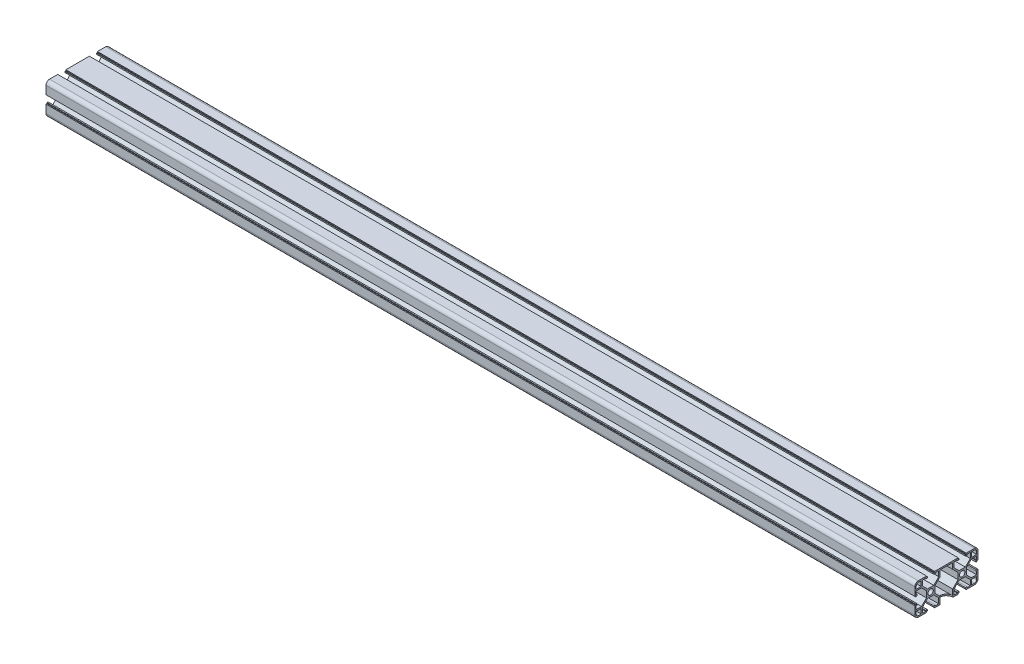
SolidWorks part; units mm, degrees
material "6063-T5"
ref_plane "前视基准面" through (0, 0, 0) normal (0, 0, 1) x (1, 0, 0)
ref_plane "上视基准面" through (0, 0, 0) normal (0, 1, 0) x (1, 0, 0)
ref_plane "右视基准面" through (0, 0, 0) normal (1, 0, 0) x (0, 0, -1)
sketch "草图1" plane through (0, 0, 0) normal (0, 1, 0) x (1, 0, 0)
  line L0 (0, 0) -> (1100, 0)
  dimension "D1" = 1100
ref_plane "基准面4" through (0, 0, 0) normal (1, 0, 0) x (0, 0, -1)
ref_plane "基准面5" through (0, 0, 0) normal (1, 0, 0) x (0, 0, -1)
ref_plane "基准面6" through (0, 0, 0) normal (1, 0, 0) x (0, 0, -1)
ref_plane "基准面7" through (0, 0, 0) normal (1, 0, 0) x (0, 0, -1)
ref_plane "基准面8" through (0, 0, 0) normal (1, 0, 0) x (0, 0, -1)
ref_plane "基准面10" through (0, 0, 0) normal (1, 0, 0) x (0, 0, -1)
other "欧标4080-厚2.0 欧标4080-厚2.0(1)"
ref_plane "基准面11" through (0, 0, 0) normal (1, 0, 0) x (0, 0, -1)
sketch "草图110" plane through (0, 0, 0) normal (1, 0, 0) x (0, 0, -1)
  line L0 (0, 20) -> (0, -20) construction
  line L1 (0, 0) -> (-20, 0) construction
  line L2 (-5.25, -3.9772) -> (-5.25, 3.9772)
  line L3 (-5.25, 3.9772) -> (-11.5228, 10.25)
  line L4 (-11.5228, 10.25) -> (-18.2, 10.25)
  line L5 (-18.2, 10.25) -> (-18.2, 6.1)
  line L6 (-18.2, 6.1) -> (-17.3, 6.1)
  line L7 (-17.3, 6.1) -> (-17.3, 4.1)
  line L8 (-17.3, 4.1) -> (-18.8, 4.1)
  line L9 (-18.8, 4.1) -> (-18.8, 5.1)
  line L10 (-18.8, 5.1) -> (-20, 5.1)
  line L11 (-20, 5.1) -> (-20, 15.5)
  line L12 (-20, 20) -> (0, 0) construction
  line L13 (-12.05, 12.05) -> (-18.2, 12.05)
  line L14 (-18.2, 12.05) -> (-18.2, 15.5)
  line L15 (-3.9772, 5.25) -> (-10.25, 11.5228)
  line L16 (3.9772, 5.25) -> (-3.9772, 5.25)
  line L17 (-12.05, 18.2) -> (-15.5, 18.2)
  line L18 (-12.05, 12.05) -> (-12.05, 18.2)
  line L19 (-5.1, 20) -> (-15.5, 20)
  line L20 (-5.1, 18.8) -> (-5.1, 20)
  line L21 (-4.1, 18.8) -> (-5.1, 18.8)
  line L22 (-4.1, 17.3) -> (-4.1, 18.8)
  line L23 (-6.1, 17.3) -> (-4.1, 17.3)
  line L24 (-6.1, 18.2) -> (-6.1, 17.3)
  line L25 (-10.25, 18.2) -> (-6.1, 18.2)
  line L26 (-10.25, 11.5228) -> (-10.25, 18.2)
  line L27 (3.9772, 5.25) -> (10.25, 11.5228)
  line L28 (5.25, 3.9772) -> (11.5228, 10.25)
  line L29 (5.25, -3.9772) -> (5.25, 3.9772)
  line L30 (20, 20) -> (20, -20) construction
  line L31 (12.05, 12.05) -> (12.05, 10.7772)
  line L32 (15.5, 20) -> (24.5, 20)
  line L33 (15.5, 18.2) -> (24.5, 18.2)
  line L34 (12.05, 10.7772) -> (11.5228, 10.25)
  line L35 (12.05, -10.7772) -> (11.5228, -10.25)
  line L36 (12.05, -12.05) -> (12.05, -10.7772)
  line L37 (15.5, -18.2) -> (24.5, -18.2)
  line L38 (15.5, -20) -> (24.5, -20)
  line L39 (60, -20) -> (40, 0) construction
  line L40 (10.25, 11.5228) -> (10.25, 18.2)
  line L41 (10.25, 18.2) -> (6.1, 18.2)
  line L42 (6.1, 18.2) -> (6.1, 17.3)
  line L43 (6.1, 17.3) -> (4.1, 17.3)
  line L44 (4.1, 17.3) -> (4.1, 18.8)
  line L45 (4.1, 18.8) -> (5.1, 18.8)
  line L46 (5.1, 18.8) -> (5.1, 20)
  line L47 (5.1, 20) -> (15.5, 20)
  line L48 (12.05, 12.05) -> (12.05, 18.2)
  line L49 (12.05, 18.2) -> (15.5, 18.2)
  line L50 (20, 20) -> (0, 0) construction
  line L51 (-17.3, -4.1) -> (-18.8, -4.1)
  line L52 (20, -20) -> (0, 0) construction
  line L53 (-20, -20) -> (0, 0) construction
  line L54 (12.05, -18.2) -> (15.5, -18.2)
  line L55 (12.05, -12.05) -> (12.05, -18.2)
  line L56 (5.1, -20) -> (15.5, -20)
  line L57 (5.1, -18.8) -> (5.1, -20)
  line L58 (4.1, -18.8) -> (5.1, -18.8)
  line L59 (4.1, -17.3) -> (4.1, -18.8)
  line L60 (6.1, -17.3) -> (4.1, -17.3)
  line L61 (6.1, -18.2) -> (6.1, -17.3)
  line L62 (10.25, -18.2) -> (6.1, -18.2)
  line L63 (10.25, -11.5228) -> (10.25, -18.2)
  line L64 (20, -20) -> (40, 0) construction
  line L65 (20, 20) -> (40, 0) construction
  line L66 (60, 20) -> (40, 0) construction
  line L67 (40, 0) -> (60, 0) construction
  line L68 (40, 20) -> (40, -20) construction
  line L69 (45.25, -3.9772) -> (51.5228, -10.25)
  line L70 (51.5228, -10.25) -> (58.2, -10.25)
  line L71 (58.2, -10.25) -> (58.2, -6.1)
  line L72 (58.2, -6.1) -> (57.3, -6.1)
  line L73 (5.25, -3.9772) -> (11.5228, -10.25)
  line L74 (3.9772, -5.25) -> (10.25, -11.5228)
  line L75 (-10.25, -11.5228) -> (-10.25, -18.2)
  line L76 (-10.25, -18.2) -> (-6.1, -18.2)
  line L77 (-6.1, -18.2) -> (-6.1, -17.3)
  line L78 (-6.1, -17.3) -> (-4.1, -17.3)
  line L79 (-4.1, -17.3) -> (-4.1, -18.8)
  line L80 (-4.1, -18.8) -> (-5.1, -18.8)
  line L81 (-5.1, -18.8) -> (-5.1, -20)
  line L82 (-5.1, -20) -> (-15.5, -20)
  line L83 (-12.05, -12.05) -> (-12.05, -18.2)
  line L84 (-12.05, -18.2) -> (-15.5, -18.2)
  line L85 (3.9772, -5.25) -> (-3.9772, -5.25)
  line L86 (-3.9772, -5.25) -> (-10.25, -11.5228)
  line L87 (-18.2, -12.05) -> (-18.2, -15.5)
  line L88 (-12.05, -12.05) -> (-18.2, -12.05)
  line L89 (-20, -5.1) -> (-20, -15.5)
  line L90 (-18.8, -5.1) -> (-20, -5.1)
  line L91 (-18.8, -4.1) -> (-18.8, -5.1)
  line L92 (-17.3, -6.1) -> (-17.3, -4.1)
  line L93 (-18.2, -6.1) -> (-17.3, -6.1)
  line L94 (-18.2, -10.25) -> (-18.2, -6.1)
  line L95 (-11.5228, -10.25) -> (-18.2, -10.25)
  line L96 (-5.25, -3.9772) -> (-11.5228, -10.25)
  line L97 (57.3, -6.1) -> (57.3, -4.1)
  line L98 (58.8, -4.1) -> (58.8, -5.1)
  line L99 (58.8, -5.1) -> (60, -5.1)
  line L100 (60, -5.1) -> (60, -15.5)
  line L101 (52.05, -12.05) -> (58.2, -12.05)
  line L102 (58.2, -12.05) -> (58.2, -15.5)
  line L103 (43.9772, -5.25) -> (50.25, -11.5228)
  line L104 (36.0228, -5.25) -> (43.9772, -5.25)
  line L105 (52.05, -18.2) -> (55.5, -18.2)
  line L106 (52.05, -12.05) -> (52.05, -18.2)
  line L107 (45.1, -20) -> (55.5, -20)
  line L108 (45.1, -18.8) -> (45.1, -20)
  line L109 (44.1, -18.8) -> (45.1, -18.8)
  line L110 (44.1, -17.3) -> (44.1, -18.8)
  line L111 (46.1, -17.3) -> (44.1, -17.3)
  line L112 (46.1, -18.2) -> (46.1, -17.3)
  line L113 (50.25, -18.2) -> (46.1, -18.2)
  line L114 (50.25, -11.5228) -> (50.25, -18.2)
  line L115 (36.0228, -5.25) -> (29.75, -11.5228)
  line L116 (34.75, -3.9772) -> (28.4772, -10.25)
  line L117 (29.75, -11.5228) -> (29.75, -18.2)
  line L118 (29.75, -18.2) -> (33.9, -18.2)
  line L119 (33.9, -18.2) -> (33.9, -17.3)
  line L120 (33.9, -17.3) -> (35.9, -17.3)
  line L121 (35.9, -17.3) -> (35.9, -18.8)
  line L122 (35.9, -18.8) -> (34.9, -18.8)
  line L123 (34.9, -18.8) -> (34.9, -20)
  line L124 (34.9, -20) -> (24.5, -20)
  line L125 (27.95, -12.05) -> (27.95, -18.2)
  line L126 (27.95, -18.2) -> (24.5, -18.2)
  line L127 (57.3, -4.1) -> (58.8, -4.1)
  line L128 (27.95, 18.2) -> (24.5, 18.2)
  line L129 (27.95, 12.05) -> (27.95, 18.2)
  line L130 (34.9, 20) -> (24.5, 20)
  line L131 (34.9, 18.8) -> (34.9, 20)
  line L132 (35.9, 18.8) -> (34.9, 18.8)
  line L133 (35.9, 17.3) -> (35.9, 18.8)
  line L134 (33.9, 17.3) -> (35.9, 17.3)
  line L135 (33.9, 18.2) -> (33.9, 17.3)
  line L136 (29.75, 18.2) -> (33.9, 18.2)
  line L137 (29.75, 11.5228) -> (29.75, 18.2)
  line L138 (27.95, -12.05) -> (27.95, -10.7772)
  line L139 (27.95, -10.7772) -> (28.4772, -10.25)
  line L140 (27.95, 10.7772) -> (28.4772, 10.25)
  line L141 (27.95, 12.05) -> (27.95, 10.7772)
  line L142 (34.75, -3.9772) -> (34.75, 3.9772)
  line L143 (34.75, 3.9772) -> (28.4772, 10.25)
  line L144 (36.0228, 5.25) -> (29.75, 11.5228)
  line L145 (50.25, 11.5228) -> (50.25, 18.2)
  line L146 (50.25, 18.2) -> (46.1, 18.2)
  line L147 (46.1, 18.2) -> (46.1, 17.3)
  line L148 (46.1, 17.3) -> (44.1, 17.3)
  line L149 (44.1, 17.3) -> (44.1, 18.8)
  line L150 (44.1, 18.8) -> (45.1, 18.8)
  line L151 (45.1, 18.8) -> (45.1, 20)
  line L152 (45.1, 20) -> (55.5, 20)
  line L153 (52.05, 12.05) -> (52.05, 18.2)
  line L154 (52.05, 18.2) -> (55.5, 18.2)
  line L155 (36.0228, 5.25) -> (43.9772, 5.25)
  line L156 (43.9772, 5.25) -> (50.25, 11.5228)
  line L157 (58.2, 12.05) -> (58.2, 15.5)
  line L158 (52.05, 12.05) -> (58.2, 12.05)
  line L159 (60, 5.1) -> (60, 15.5)
  line L160 (58.8, 5.1) -> (60, 5.1)
  line L161 (58.8, 4.1) -> (58.8, 5.1)
  line L162 (57.3, 4.1) -> (58.8, 4.1)
  line L163 (57.3, 6.1) -> (57.3, 4.1)
  line L164 (58.2, 6.1) -> (57.3, 6.1)
  line L165 (58.2, 10.25) -> (58.2, 6.1)
  line L166 (51.5228, 10.25) -> (58.2, 10.25)
  line L167 (45.25, 3.9772) -> (51.5228, 10.25)
  line L168 (45.25, -3.9772) -> (45.25, 3.9772)
  circle A0 centre (0, 0) radius 3.4
  arc A1 (-20, 15.5) -> (-15.5, 20) centre (-15.5, 15.5) cw
  arc A2 (-18.2, 15.5) -> (-15.5, 18.2) centre (-15.5, 15.5) cw
  arc A3 (60, -15.5) -> (55.5, -20) centre (55.5, -15.5) cw
  arc A4 (58.2, -15.5) -> (55.5, -18.2) centre (55.5, -15.5) cw
  arc A5 (58.2, 15.5) -> (55.5, 18.2) centre (55.5, 15.5) ccw
  arc A6 (60, 15.5) -> (55.5, 20) centre (55.5, 15.5) ccw
  arc A7 (-18.2, -15.5) -> (-15.5, -18.2) centre (-15.5, -15.5) ccw
  arc A8 (-20, -15.5) -> (-15.5, -20) centre (-15.5, -15.5) ccw
  circle A9 centre (40, 0) radius 3.4
  point P35 (-18.2, 18.2)
  point P38 (0, 5.25)
  point P65 (-5.25, 0)
  point P66 (5.25, 0)
  point P119 (0, -5.25)
  point P120 (-18.2, -18.2)
  point P168 (20, -18.2)
  point P171 (20, 18.2)
  point P194 (58.2, -18.2)
  point P195 (40, -5.25)
  point P196 (34.75, 0)
  point P197 (45.25, 0)
  point P198 (40, 5.25)
  point P199 (58.2, 18.2)
  point P200 (20, 0)
  point P201 (0, 0)
  dimension "D3" = 6.8
  dimension "D14" = 4.5
  dimension "D15" = 2.7
  dimension "D2" = 40
  dimension "D4" = 10.5
  dimension "D5" = 1.8
  dimension "D6" = 8.2
  dimension "D7" = 10.2
  dimension "D8" = 1.8
  dimension "D10" = 1.5
  dimension "D11" = 1.2
  dimension "D12" = 1
  dimension "D13" = 20.5
sketch "草图13" plane through (0, -18.2, 0) normal (0, 1, 0) x (1, 0, 0)
  line L0 (1180, 20) -> (1100, 20) construction
  line L1 (1100, 12.05) -> (1100, 27.95) construction
  line L2 (1180, 11.75) -> (1100, 11.75)
  line L3 (1180, 28.25) -> (1100, 28.25)
  arc A0 (1180, 11.75) -> (1180, 28.25) centre (1180, 20) ccw
  arc A1 (1100, 28.25) -> (1100, 11.75) centre (1100, 20) ccw
  point P4 (1140, 20)
  dimension "D1" = 8.25
  dimension "D2" = 80
extrude "切除-拉伸1" cut sketch "草图13" against normal up to next
